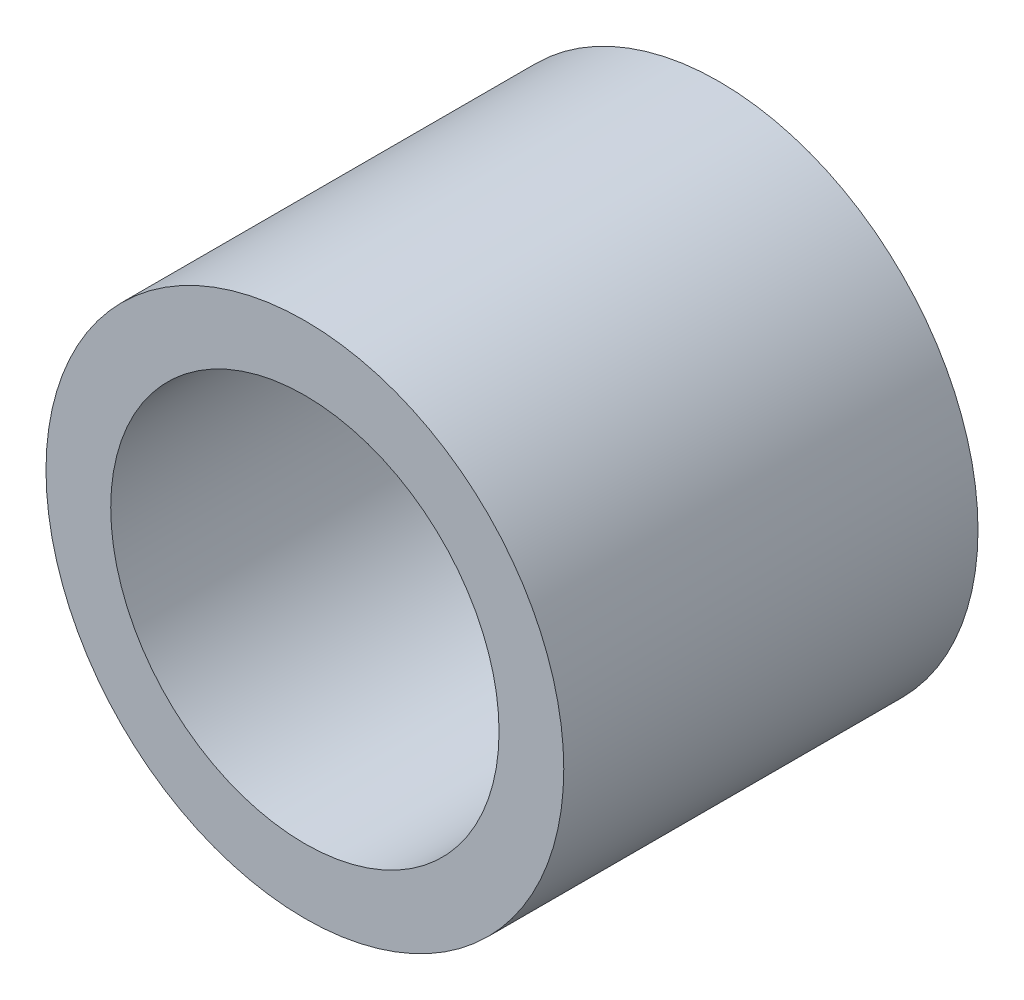
SolidWorks part; units mm, degrees
ref_plane "Front Plane" through (0, 0, 0) normal (0, 0, 1) x (1, 0, 0)
ref_plane "Top Plane" through (0, 0, 0) normal (0, 1, 0) x (1, 0, 0)
ref_plane "Right Plane" through (0, 0, 0) normal (1, 0, 0) x (0, 0, -1)
sketch "Sketch2" plane through (0, 0, 0) normal (0, 0, 1) x (1, 0, 0)
  circle A0 centre (0, 0) radius 1.5
  circle A1 centre (0, 0) radius 2
  dimension "D1" = 3
  dimension "D2" = 4
extrude "Boss-Extrude1" add sketch "Sketch2" along normal blind 3.2 contours A1 A0
